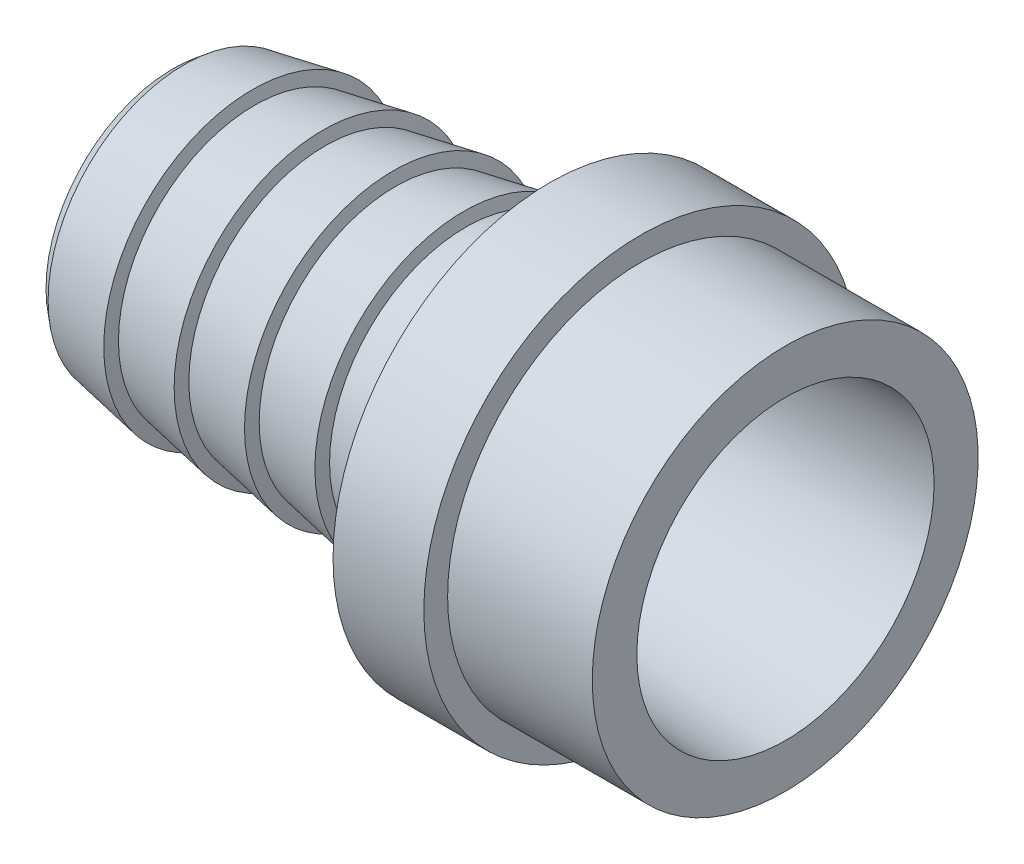
SolidWorks part; units mm, degrees
ref_plane "Front Plane" through (0, 0, 0) normal (0, 0, 1) x (1, 0, 0)
ref_plane "Top Plane" through (0, 0, 0) normal (0, 1, 0) x (1, 0, 0)
ref_plane "Right Plane" through (0, 0, 0) normal (1, 0, 0) x (0, 0, -1)
sketch "Sketch1" plane through (0, 0, 0) normal (0, 1, 0) x (1, 0, 0)
  line L0 (0, 0) -> (61.4833, 0) construction
  line L2 (-5.2397, 13.0954) -> (53.9675, 13.0954) construction
  line L3 (0, 10.0954) -> (0, 11.1836)
  line L4 (0, 11.1836) -> (1, 12)
  line L5 (1, 12) -> (7, 13.0954)
  line L6 (1, 12) -> (53.9438, 12) construction
  line L7 (7, 13.0954) -> (7.2, 12)
  line L14 (7.2, 12) -> (13.2, 13.0954)
  line L22 (13.2, 13.0954) -> (13.4, 12)
  line L23 (13.4, 12) -> (19.4, 13.0954)
  line L24 (19.4, 13.0954) -> (19.6, 12)
  line L25 (19.6, 12) -> (25.6, 13.0954)
  line L26 (25.6, 13.0954) -> (25.8, 12)
  line L27 (25.8, 12) -> (31.8, 13.0954)
  line L28 (31.8, 13.0954) -> (33.2, 13.0954)
  line L29 (31.8, 13.0954) -> (32, 12) [skipped]
  line L30 (33.2, 13.0954) -> (33.2, 19.0954)
  line L31 (33.2, 19.0954) -> (41.2, 19.0954)
  line L39 (0, 12) -> (53.9438, 12) construction
  line L40 (-5.2397, 17) -> (53.9438, 17) construction
  line L43 (41.2, 19.0954) -> (41.2, 17)
  line L44 (41.2, 17) -> (53.9438, 17)
  line L45 (53.9438, 17) -> (53.9675, 13.0954)
  line L46 (53.9675, 13.0954) -> (0, 10.0954)
  point P17 (0, 11.1836)
  point P21 (0, 10.8372)
  point P24 (41.2, 15)
  point P26 (0, 9.9069)
  point P27 (0, 10.0334)
  point P28 (0, 10.0954)
  dimension "D2" = 17
  dimension "D3" = 12
  dimension "D5" = 6
  dimension "D6" = 1
  dimension "D7" = 0.2
  dimension "D9" = 6
  dimension "D10" = 1.4
  dimension "D11" = 8
  dimension "D8" = 5
revolve "Revolve2" add sketch "Sketch1" angle 360 about L0
